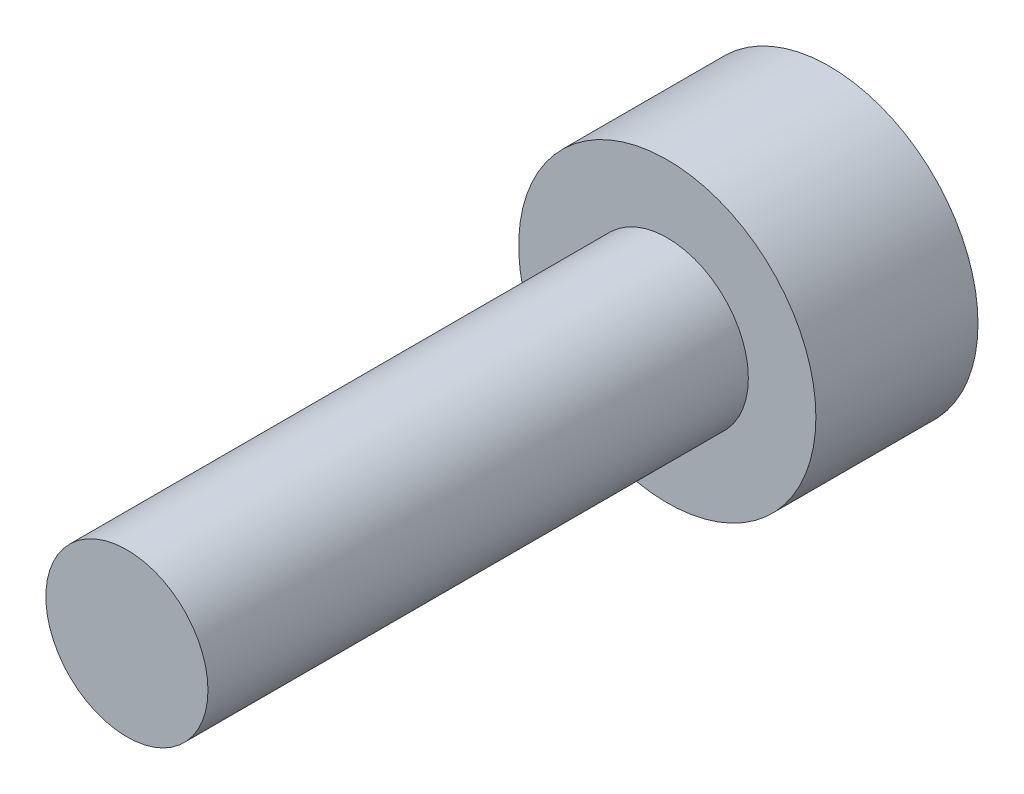
SolidWorks part; units mm, degrees
material "Acero aleado"
ref_plane "Alzado" through (0, 0, 0) normal (0, 0, 1) x (1, 0, 0)
ref_plane "Planta" through (0, 0, 0) normal (0, 1, 0) x (1, 0, 0)
ref_plane "Vista lateral" through (0, 0, 0) normal (1, 0, 0) x (0, 0, -1)
sketch "Croquis1" plane through (0, 0, 0) normal (0, 0, 1) x (1, 0, 0)
  circle A0 centre (0, 0) radius 2.75
  dimension "D1" = 5.5
extrude "Cabeza" add sketch "Croquis1" along normal blind 3 from offset 3
sketch "Croquis2" plane through (0, 0, 0) normal (0, 0, 1) x (1, 0, 0)
  circle A0 centre (0, 0) radius 1.5
  dimension "D1" = 3
extrude "Cuerpo" add sketch "Croquis2" along normal blind 10
sketch "Croquis3" plane through (0, 0, 0) normal (0, 0, 1) x (1, 0, 0)
  line L0 (1.4434, 0) -> (0.7217, 1.25)
  line L1 (0.7217, 1.25) -> (-0.7217, 1.25)
  line L2 (-0.7217, 1.25) -> (-1.4434, 0)
  line L3 (-1.4434, 0) -> (-0.7217, -1.25)
  line L4 (-0.7217, -1.25) -> (0.7217, -1.25)
  line L5 (0.7217, -1.25) -> (1.4434, 0)
  dimension "D1" = 1.4434
  dimension "D2" = 0.7217
  dimension "D3" = 1.25
  dimension "D4" = 0.7217
  dimension "D5" = 1.25
  dimension "D6" = 1.4434
  dimension "D7" = 0.7217
  dimension "D8" = 1.25
  dimension "D9" = 0.7217
  dimension "D10" = 1.25
extrude "Hexagono_interior" cut sketch "Croquis3" along normal blind 1.3 from offset 3
